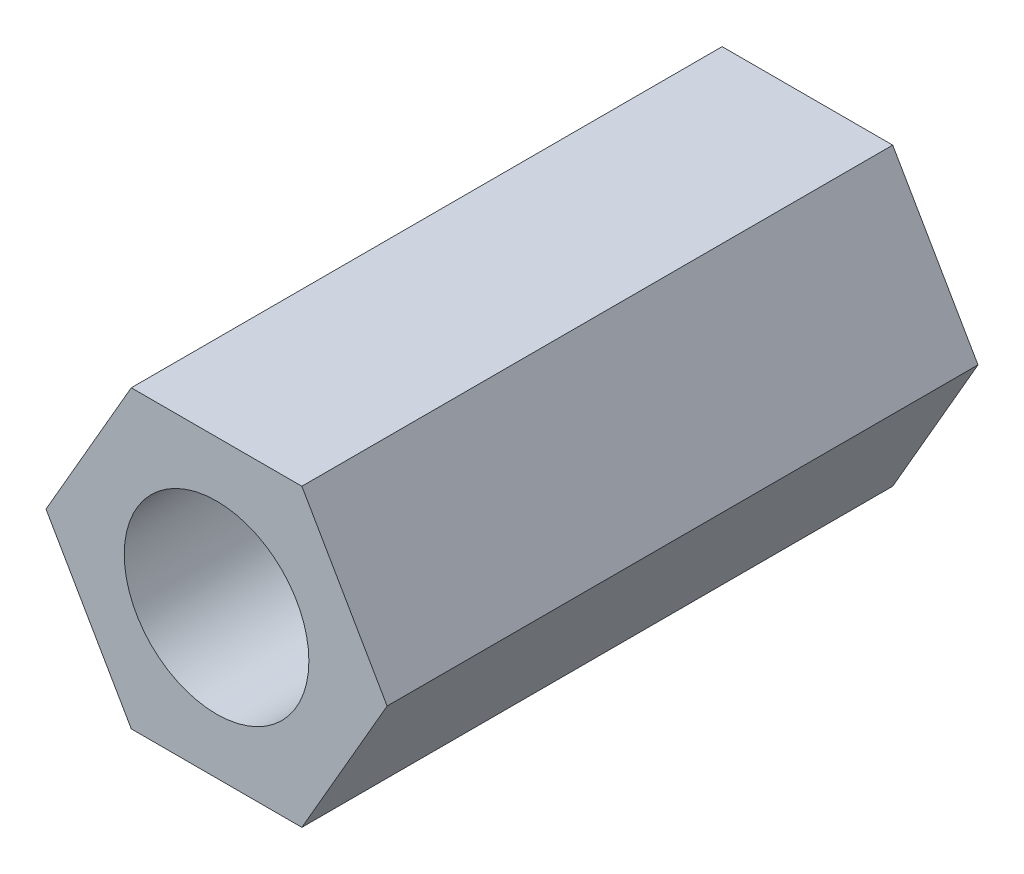
SolidWorks part; units mm, degrees
ref_plane "Front Plane" through (0, 0, 0) normal (0, 0, 1) x (1, 0, 0)
ref_plane "Top Plane" through (0, 0, 0) normal (0, 1, 0) x (1, 0, 0)
ref_plane "Right Plane" through (0, 0, 0) normal (1, 0, 0) x (0, 0, -1)
sketch "Sketch1" plane through (0, 0, 0) normal (0, 0, 1) x (1, 0, 0)
  line L1 (2.3094, 0) -> (1.1547, 2)
  line L2 (1.1547, 2) -> (-1.1547, 2)
  line L3 (-1.1547, 2) -> (-2.3094, 0)
  line L4 (-2.3094, 0) -> (-1.1547, -2)
  line L5 (-1.1547, -2) -> (1.1547, -2)
  line L6 (1.1547, -2) -> (2.3094, 0)
  circle A0 centre (0, 0) radius 2 construction
extrude "Boss-Extrude1" add sketch "Sketch1" against normal blind 8
sketch "Sketch2" plane through (0, 0, 0) normal (0, 0, 1) x (1, 0, 0)
  circle A0 centre (0, 0) radius 1.25
extrude "Cut-Extrude1" cut sketch "Sketch2" along normal through all and the other way through all
